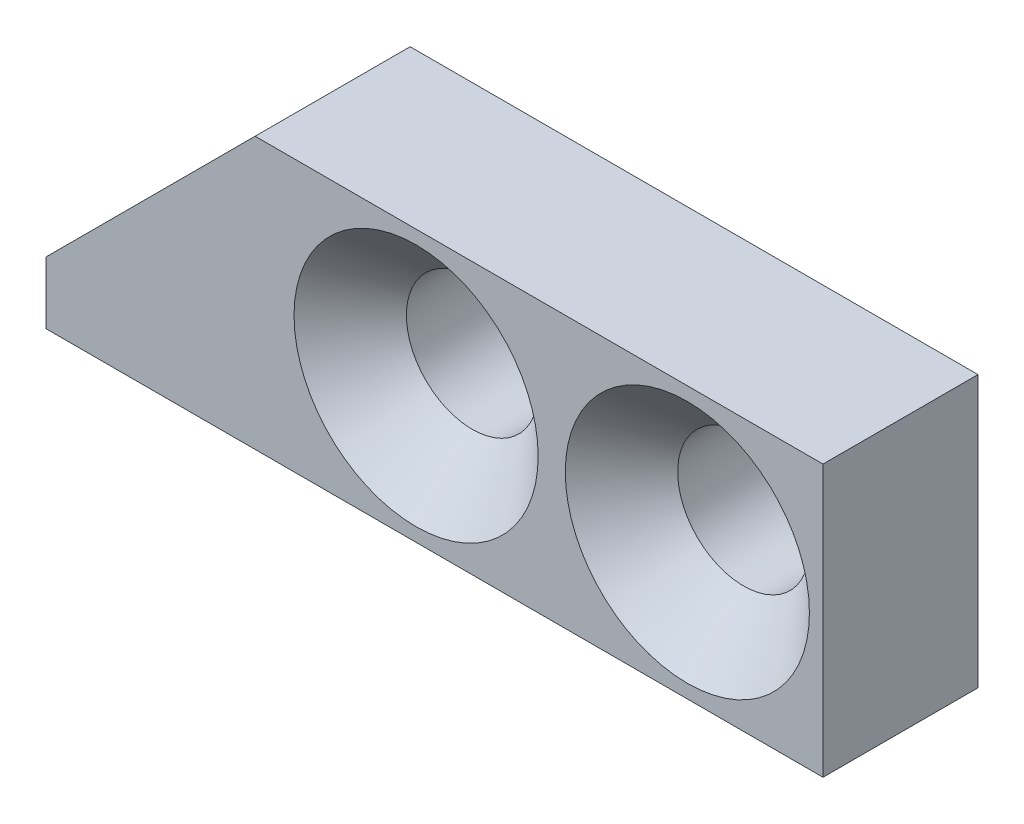
SolidWorks part; units mm, degrees
material "POLYURETHANE (11671)"
ref_plane "Front Plane" through (0, 0, 0) normal (0, 0, 1) x (1, 0, 0)
ref_plane "Top Plane" through (0, 0, 0) normal (0, 1, 0) x (1, 0, 0)
ref_plane "Right Plane" through (0, 0, 0) normal (1, 0, 0) x (0, 0, -1)
sketch "Sketch1" plane through (0, 0, 0) normal (0, 0, 1) x (1, 0, 0)
  line L1 (55, 0) -> (-55, 0) construction
  line L2 (5.3964, 7) -> (20.05, 7)
  line L3 (20.05, 7) -> (20.05, 0)
  line L4 (20.05, 0) -> (0, 0)
  line L5 (0, -55) -> (0, 55) construction
  line L6 (0, 0) -> (0, 1.6036)
  line L7 (0, 1.6036) -> (5.3964, 7)
  line L8 (0, 1.6036) -> (0, 3) construction
  line L9 (5, 7) -> (5.3964, 7) construction
  arc A1 (0, 3) -> (5, 7) centre (5, 1.875) cw construction
  point P12 (1.7984, 5.877)
  dimension "D1" = 7
  dimension "D3" = 15.05
  dimension "D4" = 5
  dimension "D2" = 3
  dimension "D5" = 45
  dimension "D6" = 1.75
extrude "Boss-Extrude1" add sketch "Sketch1" along normal blind 4
hole_wizard "CSK for M3 Countersunk Flat Head Screw1" positions "Sketch2" profile "Sketch3" countersink size "M3" standard "ISO" end condition through all
sketch "Sketch2" plane through (0, 0, 4) normal (0, 0, 1) x (1, 0, 0)
  line L0 (20.05, 0) -> (20.05, 7) construction
  line L1 (55, 0) -> (-55, 0) construction
  point P0 (16.55, 3.5)
  point P2 (9.55, 3.5)
  dimension "D1" = 7
  dimension "D2" = 3.5
  dimension "D3" = 3.5
sketch "Sketch3" plane through (16.55, 3.5, 4) normal (1, 0, 0) x (0, -1, 0)
  line L0 (0, 0) -> (0, 4)
  line L1 (0, 4) -> (1.7, 4)
  line L2 (1.7, 4) -> (1.7, 1.45)
  line L3 (1.7, 1.45) -> (3.15, 0)
  line L5 (3.15, 0) -> (0, 0)
  line L6 (-1.7, 1.45) -> (-3.15, 0) construction
  line L11 (0, -6.35) -> (0, 107.95) construction
  dimension "Thru Hole Dia." = 3.4
  dimension "Thru Hole Depth" = 4
  dimension "Near C'Sink Dia." = 6.3
  dimension "Near C'Sink Angle" = 90
hole_wizard "Tap Drill for M2 Tap1" positions "Sketch4" profile "Sketch5" hole size "M2" standard "DIN" end condition through all
sketch "Sketch4" plane through (-0.8018, 0.8018, 0) normal (-0.7071, 0.7071, 0) x (0.7071, 0.7071, 0)
  line L0 (8.7655, -4) -> (8.7655, 0) construction
  line L1 (8.7655, 0) -> (1.1339, 0) construction
  point P0 (4.9497, -2)
  point P3 (0, 0)
  point P6 (8.7655, -2)
  point P7 (0, 0)
  point P10 (4.9497, 0)
sketch "Sketch5" plane through (2.6982, 4.3018, 2) normal (0, 0, 1) x (-0.7071, -0.7071, 0)
  line L0 (0, 0) -> (0, 15.3114)
  line L1 (0, 15.3114) -> (0.95, 15.3114)
  line L2 (0.95, 15.3114) -> (0.95, 0)
  line L5 (0.95, 0) -> (0, 0)
  line L11 (0, -6.35) -> (0, 107.95) construction
  dimension "Thru Hole Dia." = 1.9
  dimension "Thru Hole Depth" = 15.3114
equation "\"D3@Sketch1\"=13.750mm+1.3"
